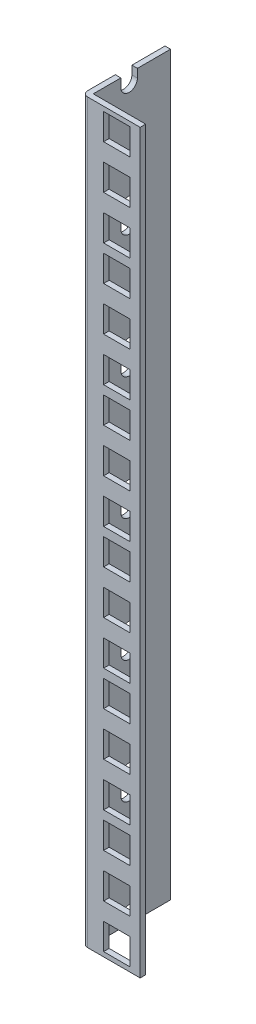
SolidWorks part; units mm, degrees
ref_plane "Front Plane" through (0, 0, 0) normal (0, 0, 1) x (1, 0, 0)
ref_plane "Top Plane" through (0, 0, 0) normal (0, 1, 0) x (1, 0, 0)
ref_plane "Right Plane" through (0, 0, 0) normal (1, 0, 0) x (0, 0, -1)
sketch "Sketch1" plane through (0, 0, 0) normal (1, 0, 0) x (0, 0, -1)
  line L0 (0, 266.8) -> (0, 0)
  line L1 (0, 0) -> (30, 0)
  line L2 (30, 0) -> (30, 266.8)
  line L3 (30, 266.8) -> (0, 266.8)
extrude "Boss-Extrude1" add sketch "Sketch1" against normal blind 21
sketch "Sketch2" plane through (0, 266.8, 0) normal (0, 1, 0) x (-1, 0, 0)
  line L0 (19, -30) -> (19, -2)
  line L1 (19, -2) -> (0, -2)
  line L2 (0, -2) -> (0, -30)
  line L3 (0, -30) -> (19, -30)
extrude "Cut-Extrude1" cut sketch "Sketch2" against normal through all
sketch "Sketch3" plane through (-19, 0, 0) normal (1, 0, 0) x (0, 0, -1)
  line L0 (12, 266.8) -> (12, 263.75)
  line L1 (18, 263.75) -> (18, 266.8)
  line L2 (18, 266.8) -> (12, 266.8)
  arc A0 (12, 263.75) -> (18, 263.75) centre (15, 263.75) ccw
extrude "Cut-Extrude2" cut sketch "Sketch3" against normal through all
sketch "Sketch4" plane through (-19, 0, 0) normal (1, 0, 0) x (0, 0, -1)
  line L0 (18, 0) -> (18, 3.05)
  line L1 (12, 3.05) -> (12, 0)
  line L2 (12, 0) -> (18, 0)
  arc A0 (18, 3.05) -> (12, 3.05) centre (15, 3.05) ccw
extrude "Cut-Extrude3" cut sketch "Sketch4" against normal through all
sketch "Sketch5" plane through (-21, 0, 0) normal (-1, 0, 0) x (0, 0, 1)
  line L0 (-12, 41.5) -> (-12, 47.5)
  line L1 (-18, 47.5) -> (-18, 41.5)
  arc A0 (-18, 41.5) -> (-12, 41.5) centre (-15, 41.5) ccw
  arc A1 (-12, 47.5) -> (-18, 47.5) centre (-15, 47.5) ccw
extrude "Cut-Extrude4" cut sketch "Sketch5" against normal through all
sketch "Sketch6" plane through (-21, 0, 0) normal (-1, 0, 0) x (0, 0, 1)
  line L0 (-12, 85.95) -> (-12, 91.95)
  line L1 (-18, 91.95) -> (-18, 85.95)
  arc A0 (-18, 85.95) -> (-12, 85.95) centre (-15, 85.95) ccw
  arc A1 (-12, 91.95) -> (-18, 91.95) centre (-15, 91.95) ccw
extrude "Cut-Extrude5" cut sketch "Sketch6" against normal through all
sketch "Sketch7" plane through (-21, 0, 0) normal (-1, 0, 0) x (0, 0, 1)
  line L0 (-12, 130.4) -> (-12, 136.4)
  line L1 (-18, 136.4) -> (-18, 130.4)
  arc A0 (-18, 130.4) -> (-12, 130.4) centre (-15, 130.4) ccw
  arc A1 (-12, 136.4) -> (-18, 136.4) centre (-15, 136.4) ccw
extrude "Cut-Extrude6" cut sketch "Sketch7" against normal through all
sketch "Sketch8" plane through (-21, 0, 0) normal (-1, 0, 0) x (0, 0, 1)
  line L0 (-12, 174.85) -> (-12, 180.85)
  line L1 (-18, 180.85) -> (-18, 174.85)
  arc A0 (-18, 174.85) -> (-12, 174.85) centre (-15, 174.85) ccw
  arc A1 (-12, 180.85) -> (-18, 180.85) centre (-15, 180.85) ccw
extrude "Cut-Extrude7" cut sketch "Sketch8" against normal through all
sketch "Sketch9" plane through (0, 0, 0) normal (0, 0, 1) x (1, 0, 0)
  line L0 (-3.75, 249.275) -> (-13.25, 249.275)
  line L1 (-13.25, 249.275) -> (-13.25, 239.775)
  line L2 (-13.25, 239.775) -> (-3.75, 239.775)
  line L3 (-3.75, 239.775) -> (-3.75, 249.275)
extrude "Cut-Extrude8" cut sketch "Sketch9" against normal through all
sketch "Sketch10" plane through (0, 0, 0) normal (0, 0, 1) x (1, 0, 0)
  line L0 (-3.75, 233.4) -> (-13.25, 233.4)
  line L1 (-13.25, 233.4) -> (-13.25, 223.9)
  line L2 (-13.25, 223.9) -> (-3.75, 223.9)
  line L3 (-3.75, 223.9) -> (-3.75, 233.4)
extrude "Cut-Extrude9" cut sketch "Sketch10" against normal through all
sketch "Sketch11" plane through (0, 0, 0) normal (0, 0, 1) x (1, 0, 0)
  line L0 (-3.75, 220.7) -> (-13.25, 220.7)
  line L1 (-13.25, 220.7) -> (-13.25, 211.2)
  line L2 (-13.25, 211.2) -> (-3.75, 211.2)
  line L3 (-3.75, 211.2) -> (-3.75, 220.7)
extrude "Cut-Extrude10" cut sketch "Sketch11" against normal through all
sketch "Sketch12" plane through (0, 0, 0) normal (0, 0, 1) x (1, 0, 0)
  line L0 (-3.75, 204.825) -> (-13.25, 204.825)
  line L1 (-13.25, 204.825) -> (-13.25, 195.325)
  line L2 (-13.25, 195.325) -> (-3.75, 195.325)
  line L3 (-3.75, 195.325) -> (-3.75, 204.825)
extrude "Cut-Extrude11" cut sketch "Sketch12" against normal through all
sketch "Sketch13" plane through (0, 0, 0) normal (0, 0, 1) x (1, 0, 0)
  line L0 (-3.75, 188.95) -> (-13.25, 188.95)
  line L1 (-13.25, 188.95) -> (-13.25, 179.45)
  line L2 (-13.25, 179.45) -> (-3.75, 179.45)
  line L3 (-3.75, 179.45) -> (-3.75, 188.95)
extrude "Cut-Extrude12" cut sketch "Sketch13" against normal through all
sketch "Sketch14" plane through (0, 0, 0) normal (0, 0, 1) x (1, 0, 0)
  line L0 (-3.75, 176.25) -> (-13.25, 176.25)
  line L1 (-13.25, 176.25) -> (-13.25, 166.75)
  line L2 (-13.25, 166.75) -> (-3.75, 166.75)
  line L3 (-3.75, 166.75) -> (-3.75, 176.25)
extrude "Cut-Extrude13" cut sketch "Sketch14" against normal through all
sketch "Sketch15" plane through (0, 0, 0) normal (0, 0, 1) x (1, 0, 0)
  line L0 (-3.75, 160.375) -> (-13.25, 160.375)
  line L1 (-13.25, 160.375) -> (-13.25, 150.875)
  line L2 (-13.25, 150.875) -> (-3.75, 150.875)
  line L3 (-3.75, 150.875) -> (-3.75, 160.375)
extrude "Cut-Extrude14" cut sketch "Sketch15" against normal through all
sketch "Sketch16" plane through (0, 0, 0) normal (0, 0, 1) x (1, 0, 0)
  line L0 (-3.75, 144.5) -> (-13.25, 144.5)
  line L1 (-13.25, 144.5) -> (-13.25, 135)
  line L2 (-13.25, 135) -> (-3.75, 135)
  line L3 (-3.75, 135) -> (-3.75, 144.5)
extrude "Cut-Extrude15" cut sketch "Sketch16" against normal through all
sketch "Sketch17" plane through (0, 0, 0) normal (0, 0, 1) x (1, 0, 0)
  line L0 (-3.75, 131.8) -> (-13.25, 131.8)
  line L1 (-13.25, 131.8) -> (-13.25, 122.3)
  line L2 (-13.25, 122.3) -> (-3.75, 122.3)
  line L3 (-3.75, 122.3) -> (-3.75, 131.8)
extrude "Cut-Extrude16" cut sketch "Sketch17" against normal through all
sketch "Sketch18" plane through (0, 0, 0) normal (0, 0, 1) x (1, 0, 0)
  line L0 (-3.75, 115.925) -> (-13.25, 115.925)
  line L1 (-13.25, 115.925) -> (-13.25, 106.425)
  line L2 (-13.25, 106.425) -> (-3.75, 106.425)
  line L3 (-3.75, 106.425) -> (-3.75, 115.925)
extrude "Cut-Extrude17" cut sketch "Sketch18" against normal through all
sketch "Sketch19" plane through (0, 0, 0) normal (0, 0, 1) x (1, 0, 0)
  line L0 (-3.75, 100.05) -> (-13.25, 100.05)
  line L1 (-13.25, 100.05) -> (-13.25, 90.55)
  line L2 (-13.25, 90.55) -> (-3.75, 90.55)
  line L3 (-3.75, 90.55) -> (-3.75, 100.05)
extrude "Cut-Extrude18" cut sketch "Sketch19" against normal through all
sketch "Sketch20" plane through (0, 0, 0) normal (0, 0, 1) x (1, 0, 0)
  line L0 (-3.75, 87.35) -> (-13.25, 87.35)
  line L1 (-13.25, 87.35) -> (-13.25, 77.85)
  line L2 (-13.25, 77.85) -> (-3.75, 77.85)
  line L3 (-3.75, 77.85) -> (-3.75, 87.35)
extrude "Cut-Extrude19" cut sketch "Sketch20" against normal through all
sketch "Sketch21" plane through (0, 0, 0) normal (0, 0, 1) x (1, 0, 0)
  line L0 (-3.75, 71.475) -> (-13.25, 71.475)
  line L1 (-13.25, 71.475) -> (-13.25, 61.975)
  line L2 (-13.25, 61.975) -> (-3.75, 61.975)
  line L3 (-3.75, 61.975) -> (-3.75, 71.475)
extrude "Cut-Extrude20" cut sketch "Sketch21" against normal through all
sketch "Sketch22" plane through (0, 0, 0) normal (0, 0, 1) x (1, 0, 0)
  line L0 (-3.75, 55.6) -> (-13.25, 55.6)
  line L1 (-13.25, 55.6) -> (-13.25, 46.1)
  line L2 (-13.25, 46.1) -> (-3.75, 46.1)
  line L3 (-3.75, 46.1) -> (-3.75, 55.6)
extrude "Cut-Extrude21" cut sketch "Sketch22" against normal through all
sketch "Sketch23" plane through (0, 0, 0) normal (0, 0, 1) x (1, 0, 0)
  line L0 (-3.75, 42.9) -> (-13.25, 42.9)
  line L1 (-13.25, 42.9) -> (-13.25, 33.4)
  line L2 (-13.25, 33.4) -> (-3.75, 33.4)
  line L3 (-3.75, 33.4) -> (-3.75, 42.9)
extrude "Cut-Extrude22" cut sketch "Sketch23" against normal through all
sketch "Sketch24" plane through (0, 0, 0) normal (0, 0, 1) x (1, 0, 0)
  line L0 (-3.75, 27.025) -> (-13.25, 27.025)
  line L1 (-13.25, 27.025) -> (-13.25, 17.525)
  line L2 (-13.25, 17.525) -> (-3.75, 17.525)
  line L3 (-3.75, 17.525) -> (-3.75, 27.025)
extrude "Cut-Extrude23" cut sketch "Sketch24" against normal through all
sketch "Sketch25" plane through (0, 0, 0) normal (0, 0, 1) x (1, 0, 0)
  line L0 (-3.75, 11.15) -> (-13.25, 11.15)
  line L1 (-13.25, 11.15) -> (-13.25, 1.65)
  line L2 (-13.25, 1.65) -> (-3.75, 1.65)
  line L3 (-3.75, 1.65) -> (-3.75, 11.15)
extrude "Cut-Extrude24" cut sketch "Sketch25" against normal through all
sketch "Sketch26" plane through (0, 0, 0) normal (0, 0, 1) x (1, 0, 0)
  line L0 (-3.75, 265.15) -> (-13.25, 265.15)
  line L1 (-13.25, 265.15) -> (-13.25, 255.65)
  line L2 (-13.25, 255.65) -> (-3.75, 255.65)
  line L3 (-3.75, 255.65) -> (-3.75, 265.15)
extrude "Cut-Extrude25" cut sketch "Sketch26" against normal through all
sketch "Sketch27" plane through (-19, 0, 0) normal (1, 0, 0) x (0, 0, -1)
  line L0 (12, 225.3) -> (12, 219.3)
  line L1 (18, 219.3) -> (18, 225.3)
  arc A0 (12, 219.3) -> (18, 219.3) centre (15, 219.3) ccw
  arc A1 (18, 225.3) -> (12, 225.3) centre (15, 225.3) ccw
extrude "Cut-Extrude26" cut sketch "Sketch27" against normal through all
fillet "Fillet1" radius 0.005 1 edges at (-19, 133.4, -2)
fillet "Fillet2" radius 2.005 1 edges at (-21, 133.4, 0)
